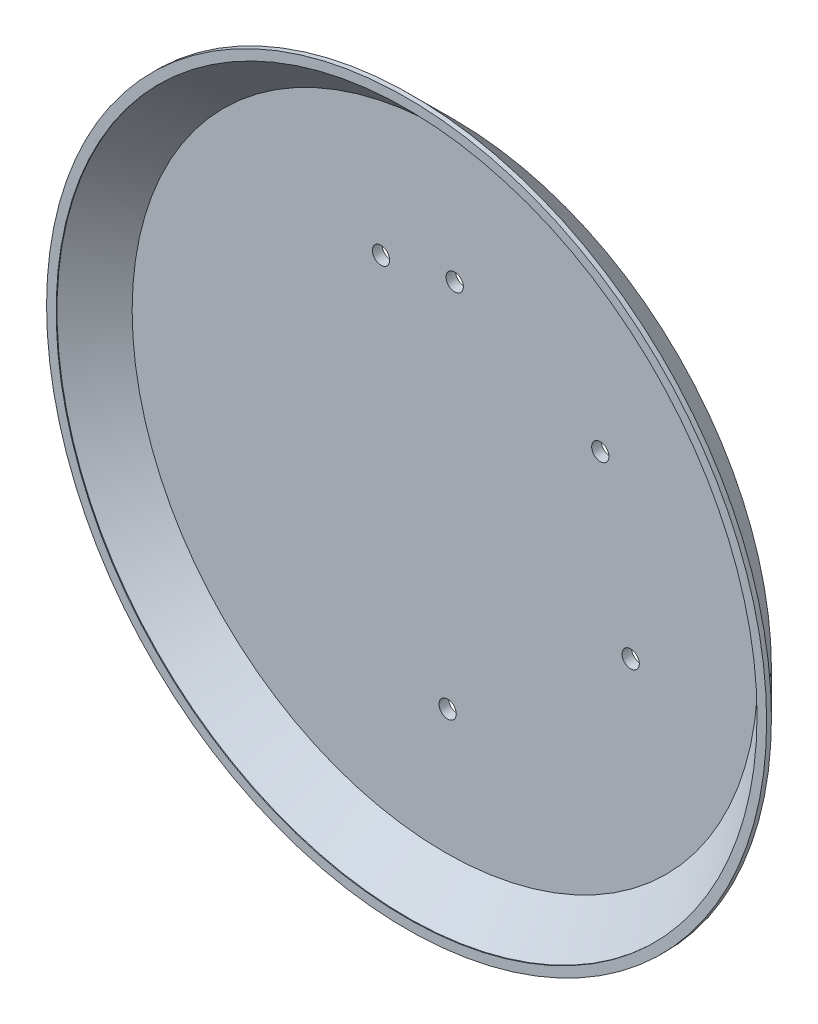
SolidWorks part; units mm, degrees
ref_plane "Front Plane" through (0, 0, 0) normal (0, 0, 1) x (1, 0, 0)
ref_plane "Top Plane" through (0, 0, 0) normal (0, 1, 0) x (1, 0, 0)
ref_plane "Right Plane" through (0, 0, 0) normal (1, 0, 0) x (0, 0, -1)
sketch "Sketch1" plane through (0, 0, 0) normal (0, 0, 1) x (1, 0, 0)
  circle A0 centre (0, 0) radius 75
  dimension "D1" = 150
extrude "Boss-Extrude1" add sketch "Sketch1" along normal blind 10
chamfer "Chamfer1" distance 9 angle 45 1 edges at (75, 0, 0)
shell "Shell1" thickness 2
sketch "Sketch2" plane through (0, 0, 2) normal (0, 0, 1) x (1, 0, 0)
  circle A0 centre (2.0151, 38.7554) radius 1.8 construction
  circle A1 centre (-13.3255, 35.9001) radius 1.8 construction
  circle A2 centre (2.0151, 38.7554) radius 1.8
  circle A3 centre (-13.3255, 35.9001) radius 1.8
  circle A4 centre (0.5488, -39.0313) radius 1.8 construction
  circle A5 centre (0.5488, -39.0313) radius 1.8
  circle A6 centre (38.6724, -10.909) radius 1.8 construction
  circle A7 centre (38.6724, -10.909) radius 1.8
  circle A8 centre (32.3464, 23.3112) radius 1.8 construction
  circle A9 centre (32.3464, 23.3112) radius 1.8
extrude "Cut-Extrude1" cut sketch "Sketch2" against normal through all
